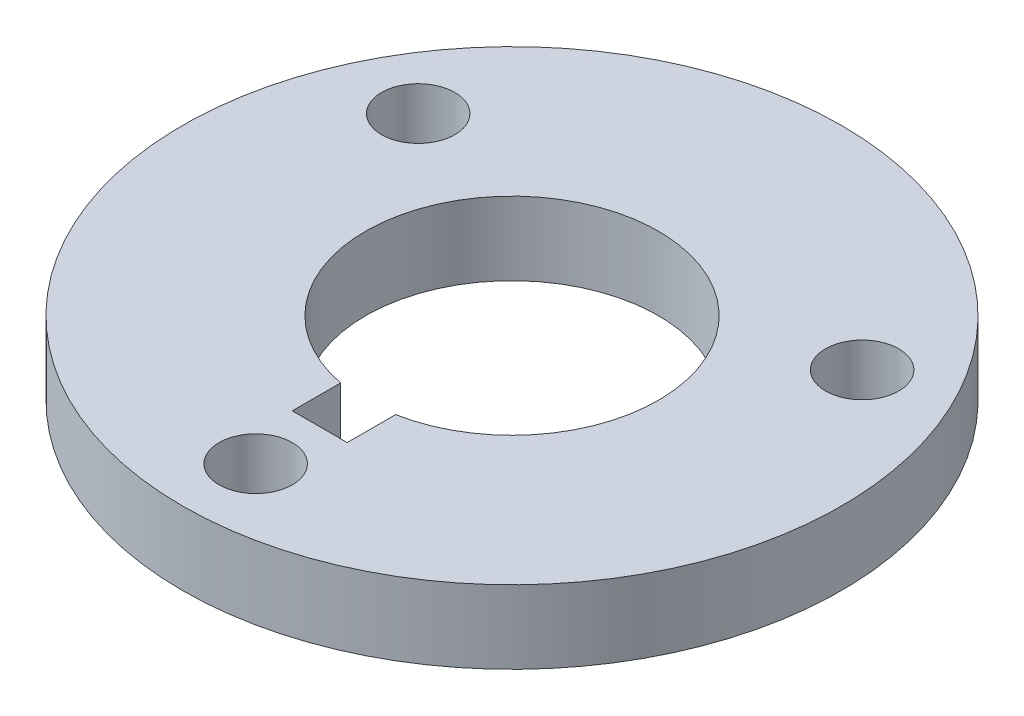
SolidWorks part; units mm, degrees
ref_plane "Front Plane" through (0, 0, 0) normal (0, 0, 1) x (1, 0, 0)
ref_plane "Top Plane" through (0, 0, 0) normal (0, 1, 0) x (1, 0, 0)
ref_plane "Right Plane" through (0, 0, 0) normal (1, 0, 0) x (0, 0, -1)
sketch "Sketch1" plane through (0, 0, 0) normal (0, 1, 0) x (1, 0, 0)
  line L1 (-1.1906, 8.3344) -> (1.1906, 8.3344)
  line L2 (-1.1906, 8.3344) -> (-1.1906, -8.3344)
  line L3 (-1.1906, -8.3344) -> (1.1906, -8.3344)
  line L4 (1.1906, 8.3344) -> (1.1906, -8.3344)
  line L5 (-1.1906, 8.3344) -> (1.1906, -8.3344) construction
  line L6 (-1.1906, -8.3344) -> (1.1906, 8.3344) construction
  line L7 (0, -11.1125) -> (9.6237, 5.5563)
  line L8 (9.6237, 5.5563) -> (-9.6237, 5.5563)
  line L9 (-9.6237, 5.5563) -> (0, -11.1125)
  circle A0 centre (0, 0) radius 14.2875
  circle A1 centre (0, 0) radius 6.35
  circle A2 centre (0, 0) radius 11.1125 construction
  circle A3 centre (-9.6237, 5.5563) radius 1.5875
  circle A4 centre (9.6237, 5.5563) radius 1.5875
  circle A5 centre (0, -11.1125) radius 1.5875
extrude "Boss-Extrude2" add sketch "Sketch1" along normal blind 3.175 contours A0 A5 L9 A1 A3 L8 L2 L1 L4 A4 L7 | A3 L9 A1 L8 | A4 L8 A1 L7 | A5 L7 A1 L4 L3 L2 L9 | A1 L4 L1 L2
